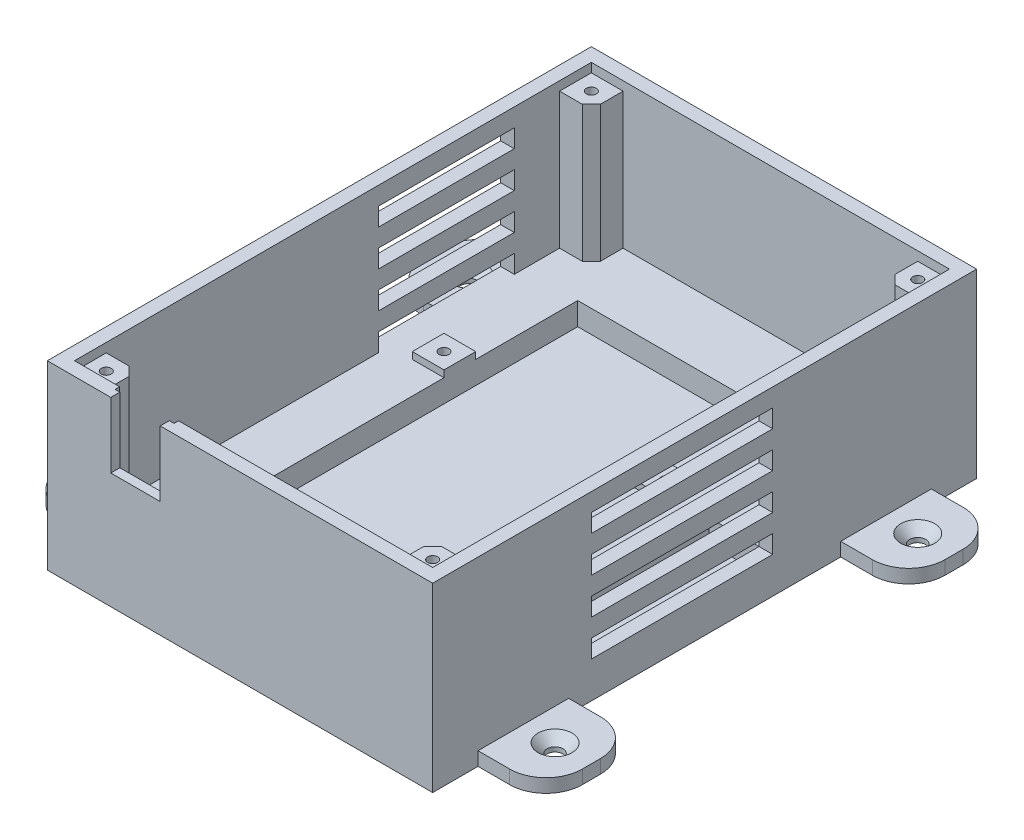
SolidWorks part; units mm, degrees
ref_plane "Спереди" through (0, 0, 0) normal (0, 0, 1) x (1, 0, 0)
ref_plane "Сверху" through (0, 0, 0) normal (0, 1, 0) x (1, 0, 0)
ref_plane "Справа" through (0, 0, 0) normal (1, 0, 0) x (0, 0, -1)
sketch "Эскиз1" plane through (0, 0, 0) normal (0, 1, 0) x (1, 0, 0)
  line L1 (42.5, -60) -> (-42.5, -60)
  line L2 (42.5, -60) -> (42.5, 60)
  line L3 (42.5, 60) -> (-42.5, 60)
  line L4 (-42.5, -60) -> (-42.5, 60)
  line L5 (42.5, -60) -> (-42.5, 60) construction
  line L6 (42.5, 60) -> (-42.5, -60) construction
  point P0 (0, 0)
  dimension "D1" = 120
  dimension "D2" = 85
extrude "Бобышка-Вытянуть1" add sketch "Эскиз1" along normal blind 40
sketch "Эскиз2" plane through (0, 40, 0) normal (0, 1, 0) x (1, 0, 0)
  line L0 (42.5, -60) -> (42.5, 60) construction
  line L1 (39.5, -57) -> (-39.5, -57)
  line L2 (39.5, -57) -> (39.5, 57)
  line L3 (39.5, 57) -> (-39.5, 57)
  line L4 (-39.5, -57) -> (-39.5, 57)
  line L5 (39.5, -57) -> (-39.5, 57) construction
  line L6 (39.5, 57) -> (-39.5, -57) construction
  line L7 (42.5, 60) -> (-42.5, 60) construction
  point P0 (0, 0)
  dimension "D1" = 3
  dimension "D2" = 3
extrude "Вырез-Вытянуть1" cut sketch "Эскиз2" against normal blind 32
sketch "Эскиз3" plane through (0, 8, 0) normal (0, 1, 0) x (1, 0, 0)
  line L0 (-39.5, 57) -> (-39.5, -57) construction
  line L1 (-27.5, 42) -> (14.5, 42)
  line L2 (-27.5, 42) -> (-27.5, -42)
  line L3 (-27.5, -42) -> (14.5, -42)
  line L4 (14.5, 42) -> (14.5, -42)
  line L5 (39.5, 57) -> (-39.5, 57) construction
  line L6 (-39.5, -57) -> (39.5, -57) construction
  dimension "D1" = 42
  dimension "D2" = 12
  dimension "D3" = 15
  dimension "D4" = 15
extrude "Вырез-Вытянуть2" cut sketch "Эскиз3" against normal blind 5
sketch "Эскиз4" plane through (0, 8, 0) normal (0, 1, 0) x (1, 0, 0)
  line L0 (-27.5, 42) -> (-27.5, -42) construction
  line L1 (-39.5, -57) -> (39.5, -57) construction
  line L2 (-34.5, 19.5) -> (-27.5, 19.5)
  line L3 (-34.5, 19.5) -> (-34.5, 12.5)
  line L4 (-34.5, 12.5) -> (-27.5, 12.5)
  line L5 (-27.5, 19.5) -> (-27.5, 12.5)
  line L6 (-34.5, 19.5) -> (-27.5, 12.5) construction
  line L7 (-34.5, 12.5) -> (-27.5, 19.5) construction
  line L8 (14.5, 19.5) -> (21.5, 19.5)
  line L9 (14.5, 19.5) -> (14.5, 12.5)
  line L10 (14.5, 12.5) -> (21.5, 12.5)
  line L11 (21.5, 19.5) -> (21.5, 12.5)
  line L12 (14.5, 19.5) -> (21.5, 12.5) construction
  line L13 (14.5, 12.5) -> (21.5, 19.5) construction
  line L14 (-34.5, -38.5) -> (-27.5, -38.5)
  line L15 (-34.5, -38.5) -> (-34.5, -45.5)
  line L16 (-34.5, -45.5) -> (-27.5, -45.5)
  line L17 (-27.5, -38.5) -> (-27.5, -45.5)
  line L18 (-34.5, -38.5) -> (-27.5, -45.5) construction
  line L19 (-34.5, -45.5) -> (-27.5, -38.5) construction
  line L20 (14.5, -38.5) -> (21.5, -38.5)
  line L21 (14.5, -38.5) -> (14.5, -45.5)
  line L22 (14.5, -45.5) -> (21.5, -45.5)
  line L23 (21.5, -38.5) -> (21.5, -45.5)
  line L24 (14.5, -38.5) -> (21.5, -45.5) construction
  line L25 (14.5, -45.5) -> (21.5, -38.5) construction
  line L26 (-39.5, -57) -> (39.5, -57) construction
  line L27 (-27.5, 42) -> (-27.5, -42) construction
  line L28 (14.5, -42) -> (14.5, 42) construction
  point P0 (-31, 16)
  point P5 (18, 16)
  point P11 (-31, -42)
  point P16 (18, -42)
  dimension "D5" = 7
  dimension "D6" = 15
  dimension "D11" = 7
  dimension "D12" = 7
  dimension "D2" = 7
  dimension "D3" = 7
  dimension "D4" = 7
  dimension "D7" = 15
  dimension "D8" = 3.5
  dimension "D9" = 7
  dimension "D10" = 7
  dimension "D13" = 3.5
  dimension "D14" = 3.5
  dimension "D15" = 58
  dimension "D16" = 58
  dimension "D17" = 3.5
extrude "Бобышка-Вытянуть2" add sketch "Эскиз4" along normal blind 1.5
sketch "Эскиз5" plane through (0, 9.5, 0) normal (0, 1, 0) x (1, 0, 0)
  line L0 (-39.5, -57) -> (39.5, -57) construction
  line L1 (-39.5, -57) -> (39.5, -57) construction
  line L2 (-27.5, 12.5) -> (-27.5, -38.5) construction
  line L3 (-27.5, 42) -> (-27.5, -42) construction
  line L4 (14.5, -42) -> (14.5, 42) construction
  line L5 (14.5, -38.5) -> (14.5, 12.5) construction
  circle A0 centre (-31, 16) radius 1.1
  circle A1 centre (18, 16) radius 1.1
  circle A2 centre (18, -42) radius 1.1
  circle A3 centre (-31, -42) radius 1.1
  dimension "D7" = 2.2
  dimension "D8" = 2.2
  dimension "D11" = 2.2
  dimension "D12" = 2.2
  dimension "D2" = 3.5
  dimension "D3" = 15
  dimension "D4" = 15
  dimension "D5" = 3.5
  dimension "D6" = 3.5
  dimension "D9" = 58
  dimension "D10" = 58
  dimension "D13" = 3.5
extrude "Вырез-Вытянуть3" cut sketch "Эскиз5" against normal blind 6
sketch "Эскиз6" plane through (0, 8, 0) normal (0, 1, 0) x (1, 0, 0)
  line L0 (-32.5, 52) -> (-34.5, 50)
  line L1 (-34.5, 50) -> (-39.5, 50)
  line L2 (-32.5, 52) -> (-32.5, 57)
  line L3 (-32.5, 57) -> (-39.5, 57)
  line L4 (-39.5, 50) -> (-39.5, 57)
  line L5 (34.5, 50) -> (32.5, 52)
  line L6 (39.5, 57) -> (32.5, 57)
  line L7 (39.5, 57) -> (39.5, 50)
  line L8 (39.5, 50) -> (34.5, 50)
  line L9 (32.5, 57) -> (32.5, 52)
  line L10 (-39.5, -57) -> (-32.5, -57)
  line L11 (-39.5, -57) -> (-39.5, -50)
  line L12 (-39.5, -50) -> (-34.5, -50)
  line L13 (-32.5, -57) -> (-32.5, -52)
  line L14 (39.5, -57) -> (32.5, -57)
  line L15 (39.5, -57) -> (39.5, -50)
  line L16 (39.5, -50) -> (34.5, -50)
  line L17 (32.5, -57) -> (32.5, -52)
  line L18 (-34.5, -50) -> (-32.5, -52)
  line L19 (34.5, -50) -> (32.5, -52)
  point P0 (-32.5, 50)
  point P8 (32.5, 50)
  point P12 (-32.5, -50)
  point P17 (32.5, -50)
  dimension "D1" = 7
  dimension "D2" = 7
  dimension "D3" = 7
  dimension "D4" = 7
  dimension "D6" = 7
  dimension "D7" = 7
  dimension "D8" = 7
  dimension "D9" = 7
extrude "Бобышка-Вытянуть3" add sketch "Эскиз6" along normal blind 30
sketch "Эскиз7" plane through (0, 38, 0) normal (0, 1, 0) x (1, 0, 0)
  line L0 (39.5, 57) -> (-39.5, 57) construction
  line L1 (39.5, 50) -> (39.5, 57) construction
  line L2 (-39.5, 57) -> (-39.5, 50) construction
  line L3 (-32.5, 57) -> (-39.5, 57) construction
  line L5 (-39.5, -57) -> (39.5, -57) construction
  line L6 (-39.5, 57) -> (-39.5, -57) construction
  line L7 (39.5, -57) -> (39.5, 57) construction
  circle A0 centre (-36, 53.5) radius 1.1
  circle A1 centre (36, 53.5) radius 1.1
  circle A2 centre (-36, -53.5) radius 1.1
  circle A3 centre (36, -53.5) radius 1.1
  dimension "D1" = 3.5
  dimension "D3" = 2.2
  dimension "D6" = 2.2
  dimension "D9" = 2.2
  dimension "D12" = 2.2
  dimension "D2" = 3.5
  dimension "D4" = 3.5
  dimension "D5" = 3.5
  dimension "D7" = 3.5
  dimension "D8" = 3.5
  dimension "D10" = 3.5
  dimension "D11" = 3.5
extrude "Вырез-Вытянуть4" cut sketch "Эскиз7" against normal blind 25
sketch "Эскиз8" plane through (0, 0, 0) normal (0, 1, 0) x (1, 0, 0)
  line L0 (-42.5, 60) -> (-42.5, -60) construction
  line L1 (-40.5, 50) -> (-49.5, 50)
  line L2 (-40.5, 50) -> (-40.5, 30)
  line L3 (-40.5, 30) -> (-49.5, 30)
  line L4 (-57.5, 42) -> (-57.5, 38)
  line L5 (42.5, 60) -> (-42.5, 60) construction
  arc A0 (-49.5, 30) -> (-57.5, 38) centre (-49.5, 38) cw
  arc A1 (-49.5, 50) -> (-57.5, 42) centre (-49.5, 42) ccw
  point P10 (-57.5, 30)
  point P13 (-57.5, 50)
  dimension "D5" = 8
  dimension "D1" = 15
  dimension "D2" = 2
  dimension "D3" = 20
  dimension "D4" = 10
extrude "Бобышка-Вытянуть4" add sketch "Эскиз8" along normal blind 3
sketch "Эскиз9" plane through (0, 3, 0) normal (0, 1, 0) x (1, 0, 0)
  line L0 (-49.5, 30) -> (-42.5, 30) construction
  line L1 (-57.5, 42) -> (-57.5, 38) construction
  circle A0 centre (-49.5, 40) radius 1.75
  dimension "D1" = 10
  dimension "D3" = 3.5
  dimension "D2" = 8
extrude "Вырез-Вытянуть5" cut sketch "Эскиз9" against normal through all
pattern_linear "Линейный массив1" count 2 spacing 80 along (0, 0, 1) of "Бобышка-Вытянуть4", "Вырез-Вытянуть5"
mirror "Зеркальное отражение1" about plane through (0, 0, 0) normal (1, 0, 0) of "Линейный массив1", "Вырез-Вытянуть5", "Бобышка-Вытянуть4"
chamfer "Фаска2" distance 2 angle 45 4 edges at (-49.5, 3, 41.75) (49.5, 3, 41.75) (49.5, 3, -38.25) (-49.5, 3, -38.25)
sketch "Эскиз10" plane through (0, 0, 60) normal (0, 0, 1) x (1, 0, 0)
  line L0 (-42.5, 40) -> (-42.5, 0) construction
  line L1 (-28.5, 42) -> (-17.6, 42)
  line L2 (-28.5, 42) -> (-28.5, 25.55)
  line L3 (-28.5, 25.55) -> (-17.6, 25.55)
  line L4 (-17.6, 42) -> (-17.6, 25.55)
  line L5 (-42.5, 40) -> (42.5, 40) construction
  dimension "D1" = 14
  dimension "D2" = 10.9
  dimension "D3" = 14.45
  dimension "D4" = 2
extrude "Вырез-Вытянуть6" cut sketch "Эскиз10" against normal blind 5
sketch "Эскиз11" plane through (0, 40, 0) normal (0, 1, 0) x (1, 0, 0)
  line L1 (-28.5, -57) -> (-28.5, -60) construction
  line L2 (-29.55, -56) -> (-16.55, -56)
  line L3 (-29.55, -56) -> (-29.55, -58)
  line L4 (-29.55, -58) -> (-16.55, -58)
  line L5 (-16.55, -56) -> (-16.55, -58)
  line L6 (-29.55, -56) -> (-16.55, -58) construction
  line L7 (-29.55, -58) -> (-16.55, -56) construction
  line L8 (-32.5, -57) -> (32.5, -57) construction
  point P0 (-23.05, -57)
  dimension "D1" = 13
  dimension "D2" = 5.45
  dimension "D3" = 1
  dimension "D4" = 2
extrude "Вырез-Вытянуть7" cut sketch "Эскиз11" against normal blind 15.5
sketch "Эскиз12" plane through (42.5, 0, 0) normal (1, 0, 0) x (0, 0, -1)
  line L0 (60, 40) -> (60, 0) construction
  line L1 (-25, 36) -> (15, 36)
  line L2 (-25, 36) -> (-25, 32)
  line L3 (-25, 32) -> (15, 32)
  line L4 (15, 36) -> (15, 32)
  line L5 (-25, 28) -> (15, 28)
  line L6 (-25, 28) -> (-25, 24)
  line L7 (-25, 24) -> (15, 24)
  line L8 (15, 28) -> (15, 24)
  line L9 (-25, 20) -> (15, 20)
  line L10 (-25, 20) -> (-25, 16)
  line L11 (-25, 16) -> (15, 16)
  line L12 (15, 20) -> (15, 16)
  line L13 (-25, 12) -> (15, 12)
  line L14 (-25, 12) -> (-25, 8)
  line L15 (-25, 8) -> (15, 8)
  line L16 (15, 12) -> (15, 8)
  line L17 (-30, 0) -> (30, 0) construction
  dimension "D1" = 45
  dimension "D2" = 40
  dimension "D3" = 45
  dimension "D4" = 40
  dimension "D5" = 45
  dimension "D6" = 40
  dimension "D7" = 45
  dimension "D8" = 40
  dimension "D9" = 4
  dimension "D10" = 4
  dimension "D11" = 4
  dimension "D12" = 4
  dimension "D13" = 8
  dimension "D14" = 4
  dimension "D15" = 4
  dimension "D16" = 4
extrude "Вырез-Вытянуть8" cut sketch "Эскиз12" against normal blind 10
sketch "Эскиз13" plane through (-42.5, 0, 0) normal (-1, 0, 0) x (0, 0, 1)
  line L0 (-60, 40) -> (-60, 0) construction
  line L1 (-40, 36) -> (-10, 36)
  line L2 (-40, 36) -> (-40, 32)
  line L3 (-40, 32) -> (-10, 32)
  line L4 (-10, 36) -> (-10, 32)
  line L5 (-40, 28) -> (-10, 28)
  line L6 (-40, 28) -> (-40, 24)
  line L7 (-40, 24) -> (-10, 24)
  line L8 (-10, 28) -> (-10, 24)
  line L9 (-40, 20) -> (-10, 20)
  line L10 (-40, 20) -> (-40, 16)
  line L11 (-40, 16) -> (-10, 16)
  line L12 (-10, 20) -> (-10, 16)
  line L13 (-40, 12) -> (-10, 12)
  line L14 (-40, 12) -> (-40, 8)
  line L15 (-40, 8) -> (-10, 8)
  line L16 (-10, 12) -> (-10, 8)
  line L17 (-30, 0) -> (30, 0) construction
  point P18 (-60, 20)
  dimension "D1" = 20
  dimension "D2" = 20
  dimension "D3" = 20
  dimension "D4" = 20
  dimension "D5" = 30
  dimension "D6" = 30
  dimension "D7" = 30
  dimension "D8" = 30
  dimension "D9" = 8
  dimension "D10" = 4
  dimension "D11" = 4
  dimension "D12" = 4
  dimension "D13" = 4
  dimension "D14" = 4
  dimension "D15" = 4
  dimension "D16" = 4
extrude "Вырез-Вытянуть9" cut sketch "Эскиз13" against normal blind 5
sketch "Эскиз14" plane through (0, 8, 0) normal (0, 1, 0) x (1, 0, 0)
  line L0 (39.5, -57) -> (39.5, 57) construction
  line L1 (39.5, 15) -> (28.5, 15)
  line L2 (39.5, 15) -> (39.5, -25)
  line L3 (39.5, -25) -> (28.5, -25)
  line L4 (28.5, 15) -> (28.5, -25)
  line L5 (32.5, 57) -> (-32.5, 57) construction
  dimension "D1" = 42
  dimension "D2" = 40
  dimension "D3" = 11
extrude "Вырез-Вытянуть10" cut sketch "Эскиз14" against normal blind 5
